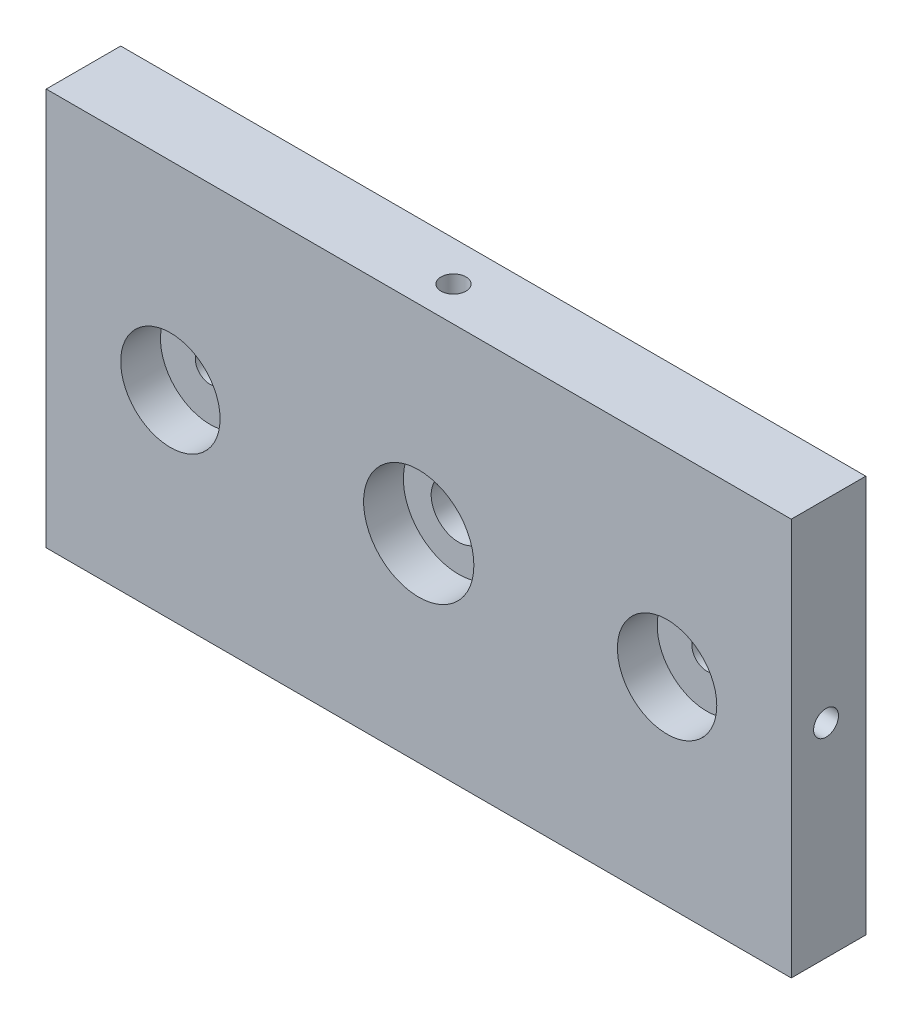
SolidWorks part; units mm, degrees
ref_plane "Front Plane" through (0, 0, 0) normal (0, 0, 1) x (1, 0, 0)
ref_plane "Top Plane" through (0, 0, 0) normal (0, 1, 0) x (1, 0, 0)
ref_plane "Right Plane" through (0, 0, 0) normal (1, 0, 0) x (0, 0, -1)
sketch "Sketch1" plane through (0, 0, 0) normal (0, 0, 1) x (1, 0, 0)
  line L0 (-75, 0) -> (75, 0) construction
  line L1 (75, -40) -> (-75, -40)
  line L2 (75, -40) -> (75, 40)
  line L3 (75, 40) -> (-75, 40)
  line L4 (-75, -40) -> (-75, 40)
  line L5 (75, -40) -> (-75, 40) construction
  line L6 (75, 40) -> (-75, -40) construction
  line L7 (0, 0) -> (0, 40) construction
  point P0 (0, 0)
  dimension "D1" = 80
  dimension "D2" = 150
extrude "Boss-Extrude1" add sketch "Sketch1" along normal blind 15
sketch "Sketch2" plane through (0, 0, 15) normal (0, 0, 1) x (1, 0, 0)
  line L0 (-75, 0) -> (75, 0) construction
  line L1 (-75, 40) -> (-75, -40) construction
  line L2 (75, -40) -> (75, 40) construction
  line L3 (0, 0) -> (0, 40) construction
  line L4 (75, 40) -> (-75, 40) construction
  circle A1 centre (-50, 0) radius 3
  circle A2 centre (50, 0) radius 3
  circle A3 centre (0, 0) radius 5.5
  dimension "D1" = 11
  dimension "D2" = 6
  dimension "D3" = 50
extrude "Cut-Extrude1" cut sketch "Sketch2" against normal up to next
sketch "Sketch3" plane through (0, 0, 15) normal (0, 0, 1) x (1, 0, 0)
  circle A0 centre (0, 0) radius 11.1
  circle A1 centre (-50, 0) radius 10
  circle A2 centre (50, 0) radius 10
  dimension "D1" = 22.2
  dimension "D2" = 20
  dimension "D3" = 20
extrude "Cut-Extrude2" cut sketch "Sketch3" against normal blind 8
sketch "Sketch5" plane through (0, 0, 0) normal (0, 0, -1) x (-1, 0, 0)
  circle A0 centre (-50, 0) radius 5
  circle A1 centre (50, 0) radius 5
  dimension "D1" = 10
  dimension "D2" = 10
extrude "Cut-Extrude4" cut sketch "Sketch5" against normal blind 4
sketch "Sketch6" plane through (-75, 0, 0) normal (-1, 0, 0) x (0, 0, 1)
  line L2 (0, 40) -> (0, -40) construction
  line L3 (15, -40) -> (0, -40) construction
  circle A0 centre (8, 1) radius 2.5
  dimension "D2" = 5
  dimension "D1" = 8
  dimension "D3" = 41
extrude "Cut-Extrude5" cut sketch "Sketch6" against normal blind 10
mirror "Mirror1" about plane through (0, 0, 0) normal (1, 0, 0) of "Cut-Extrude5"
sketch "Sketch7" plane through (0, -40, 0) normal (0, -1, 0) x (1, 0, 0)
  line L0 (0, 0) -> (0, 15) construction
  line L1 (-75, 15) -> (75, 15) construction
  line L2 (-75, 15) -> (-75, 0) construction
  circle A0 centre (-62, 8) radius 2.5
  circle A1 centre (62, 8) radius 2.5
  dimension "D1" = 5
  dimension "D2" = 7
  dimension "D3" = 13
extrude "Cut-Extrude6" cut sketch "Sketch7" against normal blind 10
sketch "Sketch8" plane through (0, 40, 0) normal (0, 1, 0) x (1, 0, 0)
  line L0 (0, 0) -> (0, -15) construction
  line L1 (75, 0) -> (-75, 0) construction
  line L2 (75, -15) -> (-75, -15) construction
  circle A0 centre (0, -8) radius 2.5
  dimension "D1" = 5
  dimension "D2" = 8
extrude "Cut-Extrude7" cut sketch "Sketch8" against normal blind 10
